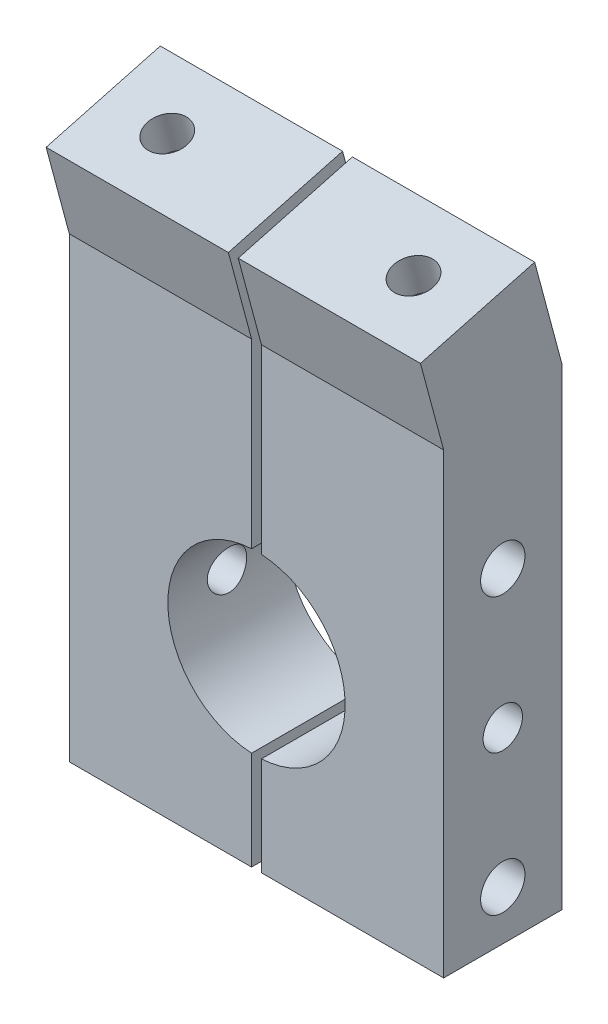
SolidWorks part; units mm, degrees
ref_plane "Front Plane" through (0, 0, 0) normal (0, 0, 1) x (1, 0, 0)
ref_plane "Top Plane" through (0, 0, 0) normal (0, 1, 0) x (1, 0, 0)
ref_plane "Right Plane" through (0, 0, 0) normal (1, 0, 0) x (0, 0, -1)
sketch "Sketch1" plane through (0, 0, 0) normal (0, 0, 1) x (1, 0, 0)
  line L0 (0, 0) -> (0, -5) construction
  line L1 (-19, 24) -> (19, 24)
  line L2 (-19, 24) -> (-19, -24)
  line L3 (-19, -24) -> (19, -24)
  line L4 (19, 24) -> (19, -24)
  line L5 (-19, 24) -> (19, -24) construction
  line L6 (-19, -24) -> (19, 24) construction
  circle A0 centre (0, -5) radius 9
  point P0 (0, 0)
  dimension "D4" = 18
  dimension "D1" = 48
  dimension "D2" = 38
  dimension "D3" = 19
extrude "Boss-Extrude1" add sketch "Sketch1" along normal blind 12
sketch "Sketch2" plane through (0, 0, 0) normal (1, 0, 0) x (0, 0, -1)
  line L0 (-6, 24) -> (-6, -24) construction
  line L1 (-12, 24) -> (0, 24) construction
  line L2 (-12, -24) -> (0, -24) construction
  circle A0 centre (-6, -19) radius 2.25
  circle A1 centre (-6, -5) radius 2
  circle A2 centre (-6, 9) radius 2.25
  dimension "D4" = 4.5
  dimension "D5" = 4
  dimension "D1" = 5
  dimension "D2" = 19
  dimension "D3" = 33
extrude "Cut-Extrude1" cut sketch "Sketch2" against normal through all both and the other way through all
sketch "Sketch5" plane through (0, 0, 0) normal (0, 0, 1) x (1, 0, 0)
  line L0 (19, -5) -> (-19, -5) construction
  line L1 (19, -24) -> (19, 24) construction
  line L2 (-19, 24) -> (-19, -24) construction
  line L3 (19, -3) -> (8.775, -3) construction
  line L4 (8.775, -7) -> (19, -7) construction
  line L23 (15.35, -1.25) -> (12.65, -1.25)
  line L24 (15.35, -1.25) -> (15.35, -8.75)
  line L25 (15.35, -8.75) -> (12.65, -8.75)
  line L26 (12.65, -1.25) -> (12.65, -8.75)
  line L27 (15.35, -1.25) -> (12.65, -8.75) construction
  line L28 (15.35, -8.75) -> (12.65, -1.25) construction
  line L29 (-12.65, -1.25) -> (-15.35, -1.25)
  line L30 (-12.65, -1.25) -> (-12.65, -8.75)
  line L31 (-12.65, -8.75) -> (-15.35, -8.75)
  line L32 (-15.35, -1.25) -> (-15.35, -8.75)
  line L33 (-12.65, -1.25) -> (-15.35, -8.75) construction
  line L34 (-12.65, -8.75) -> (-15.35, -1.25) construction
  point P30 (14, -5)
  point P35 (-14, -5)
  dimension "D1" = 5
  dimension "D2" = 5
  dimension "D5" = 2.7
  dimension "D6" = 7.5
extrude "Cut-Extrude4" cut sketch "Sketch5" along normal blind 9.75
sketch "Sketch6" plane through (0, 0, 0) normal (1, 0, 0) x (0, 0, -1)
  line L0 (0, 24) -> (-2.7633, 34.3128)
  line L1 (-2.7633, 34.3128) -> (-14.3544, 31.207)
  line L2 (-14.3544, 31.207) -> (-12, 22.4202)
  line L3 (-12, -24) -> (-12, 24) construction
  line L4 (-12, 22.4202) -> (-12, 24)
  line L5 (-12, 24) -> (0, 24)
  line L6 (0, -24) -> (0, 24) construction
  dimension "D1" = 165
  dimension "D2" = 12
extrude "Boss-Extrude2" add sketch "Sketch6" along normal mid plane 38
sketch "Sketch4" plane through (0, 0, 0) normal (0, 0, 1) x (1, 0, 0)
  line L1 (-0.5, 34.3128) -> (0.5, 34.3128)
  line L2 (-0.5, 34.3128) -> (-0.5, -24)
  line L3 (-0.5, -24) -> (0.5, -24)
  line L4 (0.5, 34.3128) -> (0.5, -24)
  line L5 (-0.5, 34.3128) -> (0.5, -24) construction
  line L6 (-0.5, -24) -> (0.5, 34.3128) construction
  line L7 (19, 34.3128) -> (-19, 34.3128) construction
  point P0 (0, 0)
  dimension "D1" = 0.5
extrude "Cut-Extrude3" cut sketch "Sketch4" along normal through all
sketch "Sketch7" plane through (0, 32.7051, 8.7633) normal (0, 0.9659, 0.2588) x (1, 0, 0)
  line L0 (-12.5, 0.2117) -> (12.5, 0.2117) construction
  line L1 (0, 0.2117) -> (0, 0) construction
  line L2 (-0.5, -5.7883) -> (-19, -5.7883) construction
  line L3 (-0.5, 6.2117) -> (-19, 6.2117) construction
  circle A0 centre (-12.5, 0.2117) radius 2
  circle A1 centre (12.5, 0.2117) radius 2
  point P7 (0, 0.2117)
  dimension "D2" = 4
  dimension "D1" = 25
extrude "Cut-Extrude5" cut sketch "Sketch7" against normal blind 12
sketch "Sketch8" plane through (0, 1.6077, -6) normal (0, 0.2588, -0.9659) x (-1, 0, 0)
  line L0 (-12.5, 21.8588) -> (-12.5, 28.8588) construction
  line L1 (-16.25, 29.9588) -> (-8.75, 29.9588)
  line L2 (-16.25, 29.9588) -> (-16.25, 27.7588)
  line L3 (-16.25, 27.7588) -> (-8.75, 27.7588)
  line L4 (-8.75, 29.9588) -> (-8.75, 27.7588)
  line L5 (-16.25, 29.9588) -> (-8.75, 27.7588) construction
  line L6 (-16.25, 27.7588) -> (-8.75, 29.9588) construction
  line L7 (8.75, 29.9588) -> (16.25, 29.9588)
  line L8 (8.75, 29.9588) -> (8.75, 27.7588)
  line L9 (8.75, 27.7588) -> (16.25, 27.7588)
  line L10 (16.25, 29.9588) -> (16.25, 27.7588)
  line L11 (8.75, 29.9588) -> (16.25, 27.7588) construction
  line L12 (8.75, 27.7588) -> (16.25, 29.9588) construction
  line L16 (-10.5, 21.8588) -> (-14.5, 21.8588) construction
  line L17 (-12.5, 28.8588) -> (12.5, 28.8588) construction
  line L18 (12.5, 28.8588) -> (12.5, 21.8588) construction
  line L19 (14.5, 21.8588) -> (10.5, 21.8588) construction
  line L20 (-19, 33.8588) -> (-0.5, 33.8588) construction
  point P0 (-12.5, 28.8588)
  point P5 (12.5, 28.8588)
  dimension "D1" = 2.2
  dimension "D2" = 7.5
  dimension "D3" = 5
extrude "Cut-Extrude6" cut sketch "Sketch8" against normal blind 9.75
equation "\"a\"= 38"
equation "\"b\"= 48"
equation "\"c\"= 12"
equation "\"D1@Cut-Extrude4\"=\"c\"/2+3.75"
equation "\"D2@Sketch6\"=\"c\""
equation "\"D2@Sketch1\"=\"a\""
equation "\"D1@Sketch1\"=\"b\""
equation "\"D1@Boss-Extrude2\"=\"a\""
equation "\"D1@Sketch7\"=\"a\"-13"
equation "\"D1@Cut-Extrude6\"=\"c\"/2+3.75"
equation "\"D1@Boss-Extrude1\"=\"c\""
